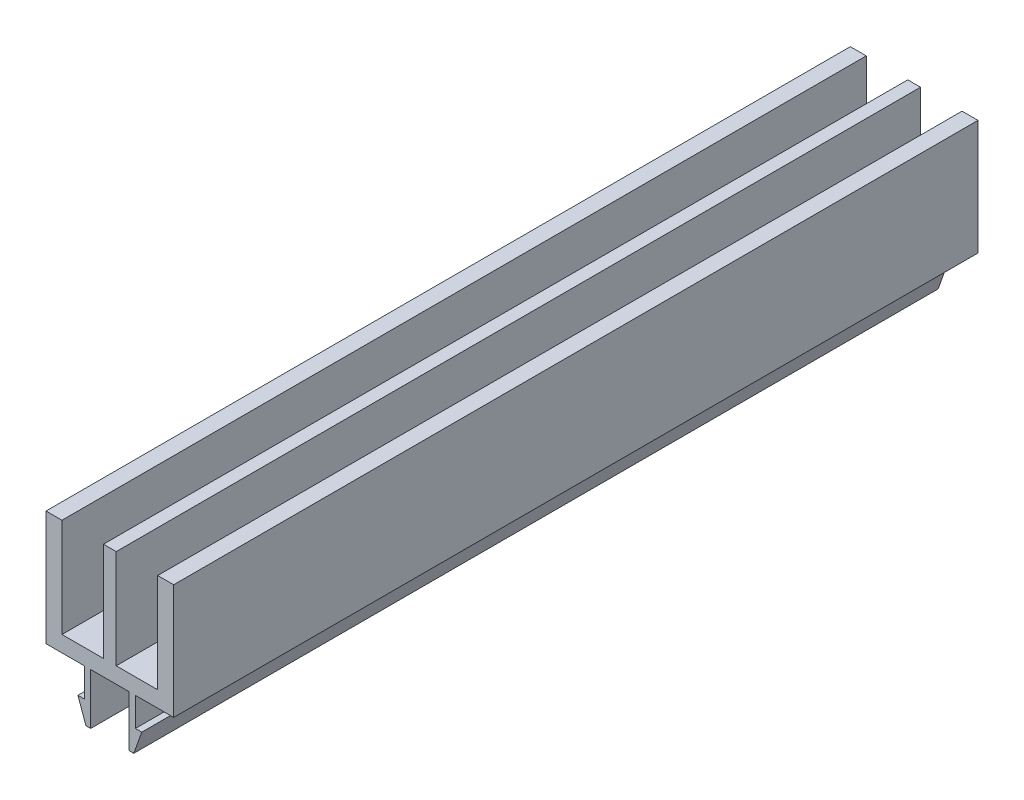
SolidWorks part; units mm, degrees
ref_plane "Plan de face" through (0, 0, 0) normal (0, 0, 1) x (1, 0, 0)
ref_plane "Plan de dessus" through (0, 0, 0) normal (0, 1, 0) x (1, 0, 0)
ref_plane "Plan de droite" through (0, 0, 0) normal (1, 0, 0) x (0, 0, -1)
ref_plane "Plan1" through (0, 0, 50) normal (0, 0, 1) x (1, 0, 0)
sketch "Esquisse1" plane through (0, 0, 50) normal (0, 0, 1) x (1, 0, 0)
  line L0 (-1, 2.5) -> (-7.5, 2.5)
  line L1 (-7.5, 2.5) -> (-7.5, 18)
  line L2 (-7.5, 18) -> (-10, 18)
  line L3 (-10, 18) -> (-10, 0)
  line L4 (-10, 0) -> (-4, 0)
  line L5 (-4, 0) -> (-4, -4.5)
  line L6 (-4, -4.5) -> (-5, -4.5)
  line L7 (-5, -4.5) -> (-3.75, -8)
  line L8 (-3.75, -8) -> (-3, -8)
  line L9 (-3, -8) -> (-3, 0)
  line L10 (-3, 0) -> (3, 0)
  line L11 (3, 0) -> (3, -8)
  line L12 (3, -8) -> (3.75, -8)
  line L13 (3.75, -8) -> (5, -4.5)
  line L14 (5, -4.5) -> (4, -4.5)
  line L15 (4, -4.5) -> (4, 0)
  line L16 (4, 0) -> (10, 0)
  line L17 (10, 0) -> (10, 18)
  line L18 (10, 18) -> (7.5, 18)
  line L19 (7.5, 18) -> (7.5, 2.5)
  line L20 (7.5, 2.5) -> (1, 2.5)
  line L21 (1, 2.5) -> (1, 18)
  line L22 (1, 18) -> (-1, 18)
  line L23 (-1, 18) -> (-1, 2.5)
extrude "Boss.-Extru.1" add sketch "Esquisse1" against normal blind 126
